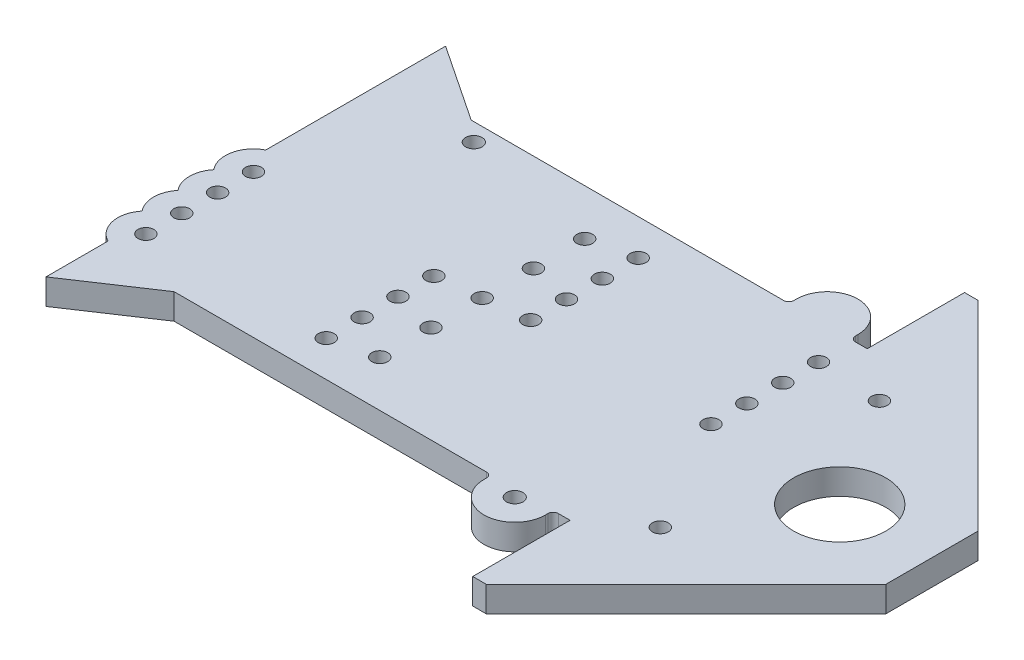
SolidWorks part; units mm, degrees
ref_plane "Front Plane" through (0, 0, 0) normal (0, 0, 1) x (1, 0, 0)
ref_plane "Top Plane" through (0, 0, 0) normal (0, 1, 0) x (1, 0, 0)
ref_plane "Right Plane" through (0, 0, 0) normal (1, 0, 0) x (0, 0, -1)
sketch "Sketch1" plane through (0, 0, 0) normal (0, 1, 0) x (1, 0, 0)
  line L0 (28.5751, 48.8215) -> (28.5751, 67.8215)
  line L2 (-63.7249, -9.1785) -> (-63.7249, -7.0775)
  line L3 (-18.8873, 18.9968) -> (28.5751, 48.8215) construction
  line L4 (-18.8873, 20.6462) -> (28.5751, -9.1785) construction
  line L5 (28.5751, -9.1785) -> (28.5751, -28.1785)
  line L6 (28.5751, 48.8215) -> (28.5751, -9.1785) construction
  line L11 (28.5751, 48.8215) -> (26.2701, 48.8215)
  line L14 (-48.7249, 48.8215) -> (-63.7249, 58.8215)
  line L15 (-63.7249, 58.8215) -> (-63.7249, 48.8215)
  line L17 (-63.7249, 19.8215) -> (-60.0406, 19.8215) construction
  line L19 (-63.7249, -19.1785) -> (-63.7249, -9.1785)
  line L20 (-48.7249, -9.1785) -> (-63.7249, -19.1785)
  line L23 (-48.7249, -9.1785) -> (12.2701, -9.1785)
  line L25 (31.2025, 67.8215) -> (70.2134, 28.8107)
  line L27 (28.5751, -28.1785) -> (31.2025, -28.1785)
  line L28 (25.2701, -10.6735) -> (25.2701, -10.1785)
  line L29 (28.5751, 67.8215) -> (31.2025, 67.8215)
  line L30 (13.2701, -10.6735) -> (13.2701, -10.1785)
  line L31 (26.2701, -9.1785) -> (28.5751, -9.1785)
  line L32 (19.2701, -10.6735) -> (24.1031, -10.6735) construction
  line L33 (13.2701, 50.3165) -> (13.2701, 49.8215)
  line L34 (25.2701, 50.3165) -> (25.2701, 49.8215)
  line L35 (12.2701, 48.8215) -> (-48.7249, 48.8215)
  line L36 (-55.8166, 19.8215) -> (68.9336, 19.8215) construction
  line L37 (-63.7249, 23.7205) -> (-63.7249, 48.8215)
  line L38 (70.2134, 28.8107) -> (70.2134, 10.8324)
  line L39 (70.2134, 10.8324) -> (31.2025, -28.1785)
  circle A0 centre (26.0751, 20.8215) radius 1.55
  circle A1 centre (-9.1249, 20.8215) radius 1.55
  circle A2 centre (-9.1249, 27.8215) radius 1.55
  circle A3 centre (26.0751, 27.8215) radius 1.55
  circle A4 centre (-9.1249, 34.8215) radius 1.55
  circle A5 centre (26.0751, 34.8215) radius 1.55
  circle A6 centre (-9.1249, 41.8215) radius 1.55
  circle A7 centre (26.0751, 41.8215) radius 1.55
  circle A8 centre (-26.0249, -2.1785) radius 1.55
  circle A9 centre (-61.2249, -2.1785) radius 1.55
  circle A10 centre (-26.0249, 4.8215) radius 1.55
  circle A11 centre (-61.2249, 4.8215) radius 1.55
  circle A12 centre (-26.0249, 11.8215) radius 1.55
  circle A13 centre (-61.2249, 11.8215) radius 1.55
  circle A14 centre (-26.0249, 18.8215) radius 1.55
  circle A15 centre (-61.2249, 18.8215) radius 1.55
  circle A16 centre (-17.5749, 39.8215) radius 1.55
  circle A17 centre (-17.5749, 29.8215) radius 1.55
  circle A18 centre (-17.5749, 19.8215) radius 1.55
  circle A19 centre (-17.5749, 9.8215) radius 1.55
  circle A20 centre (-17.5749, -0.1785) radius 1.55
  circle A26 centre (52.2134, 19.8215) radius 9
  arc A27 (13.2701, -10.6735) -> (25.2701, -10.6735) centre (19.2701, -10.6735) ccw
  arc A28 (25.2701, -10.1785) -> (26.2701, -9.1785) centre (26.2701, -10.1785) cw
  arc A29 (13.2701, -10.1785) -> (12.2701, -9.1785) centre (12.2701, -10.1785) ccw
  circle A30 centre (19.2701, -10.6735) radius 1.605
  circle A31 centre (-44.7399, 45.3465) radius 1.605
  arc A32 (13.2701, 49.8215) -> (12.2701, 48.8215) centre (12.2701, 49.8215) cw
  arc A33 (13.2701, 50.3165) -> (25.2701, 50.3165) centre (19.2701, 50.3165) cw
  arc A34 (25.2701, 49.8215) -> (26.2701, 48.8215) centre (26.2701, 49.8215) ccw
  arc A36 (-65.4675, 15.3215) -> (-65.4675, 8.3215) centre (-61.2249, 11.8215) ccw
  arc A39 (-63.7249, 23.7205) -> (-65.4675, 15.3215) centre (-61.2249, 18.8215) ccw
  arc A41 (-65.4675, 8.3215) -> (-65.4675, 1.3215) centre (-61.2249, 4.8215) ccw
  arc A43 (-65.4675, 1.3215) -> (-63.7249, -7.0775) centre (-61.2249, -2.1785) ccw
  circle A46 centre (38.5751, 41.2063) radius 1.55
  circle A47 centre (38.5751, -1.5633) radius 1.55
  point P0 (-17.5749, 19.8215)
  point P58 (25.2701, -9.1785)
  dimension "D1" = 58
  dimension "D11" = 3.1
  dimension "D10" = 3.1
  dimension "D15" = 18
  dimension "D8" = 12
  dimension "D9" = 1
  dimension "D2" = 92.3
  dimension "D3" = 19
  dimension "D4" = 19
  dimension "D5" = 2.6274
  dimension "D13" = 10
  dimension "D14" = 15
  dimension "D12" = 5
extrude "Boss-Extrude1" add sketch "Sketch1" along normal blind 5
sketch "Sketch3" plane through (0, 0, 0) normal (0, -1, 0) x (-1, 0, 0)
  circle A1 centre (61.2249, -2.1785) radius 3.05
  circle A2 centre (61.2249, 4.8215) radius 3.05
  circle A3 centre (61.2249, 11.8215) radius 3.05
  circle A4 centre (61.2249, 18.8215) radius 3.05
  circle A6 centre (26.0249, -2.1785) radius 3.05
  circle A7 centre (26.0249, 4.8215) radius 3.05
  circle A8 centre (26.0249, 11.8215) radius 3.05
  circle A9 centre (26.0249, 18.8215) radius 3.05
  circle A10 centre (17.5749, -0.1785) radius 3.05
  circle A11 centre (17.5749, 9.8215) radius 3.05
  circle A12 centre (17.5749, 19.8215) radius 3.05
  circle A13 centre (17.5749, 29.8215) radius 3.05
  circle A14 centre (17.5749, 39.8215) radius 3.05
  circle A15 centre (9.1249, 20.8215) radius 3.05
  circle A16 centre (9.1249, 27.8215) radius 3.05
  circle A17 centre (9.1249, 34.8215) radius 3.05
  circle A18 centre (9.1249, 41.8215) radius 3.05
  circle A21 centre (-26.0751, 20.8215) radius 3.05
  circle A22 centre (-26.0751, 27.8215) radius 3.05
  circle A23 centre (-26.0751, 34.8215) radius 3.05
  circle A24 centre (-26.0751, 41.8215) radius 3.05
  circle A26 centre (-19.2701, -10.6735) radius 3.05
  circle A27 centre (44.7399, 45.3465) radius 3.05
  circle A28 centre (-38.5751, 41.2063) radius 3.05
  circle A29 centre (-38.5751, -1.5633) radius 3.05
extrude "Cut-Extrude1" cut sketch "Sketch3" against normal blind 2
